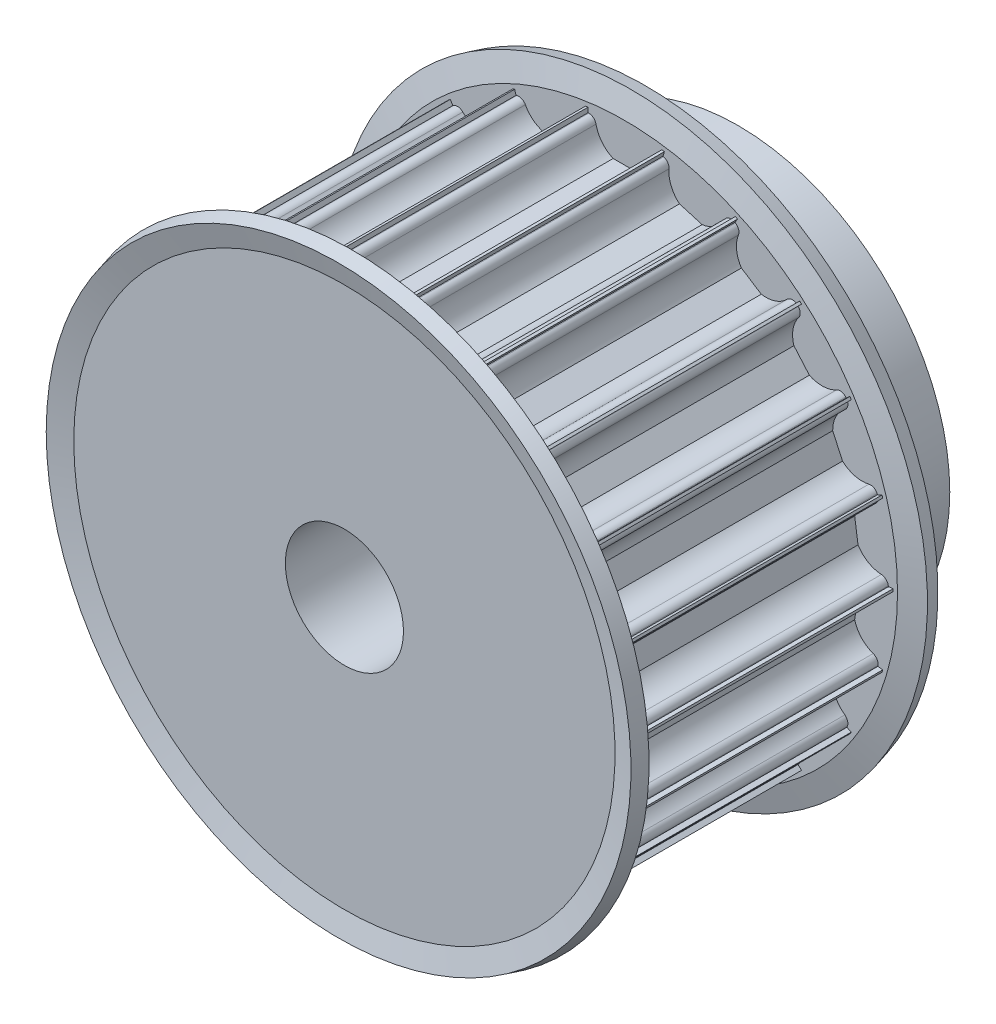
SolidWorks part; units mm, degrees
ref_plane "Front Plane" through (0, 0, 0) normal (0, 0, 1) x (1, 0, 0)
ref_plane "Top Plane" through (0, 0, 0) normal (0, 1, 0) x (1, 0, 0)
ref_plane "Right Plane" through (0, 0, 0) normal (1, 0, 0) x (0, 0, -1)
sketch "Sketch1" plane through (0, 0, 0) normal (1, 0, 0) x (0, 0, -1)
  line L0 (0, 0) -> (61.9374, 0) construction
  line L1 (0, 6) -> (0, 27.25)
  line L2 (0, 27.25) -> (30, 27.25)
  line L3 (30, 27.25) -> (30, 21.5)
  line L4 (30, 21.5) -> (40, 21.5)
  line L5 (40, 21.5) -> (40, 6)
  line L6 (40, 6) -> (0, 6)
  dimension "D1" = 27.25
  dimension "D2" = 30
  dimension "D3" = 10
  dimension "D4" = 6
  dimension "D5" = 15.5
revolve "Revolve1" add sketch "Sketch1" angle 360 about L0
sketch "Sketch2" plane through (0, 0, 0) normal (0, 0, 1) x (1, 0, 0)
  line L0 (-3.6742, 26.5) -> (-3.75, 26.5)
  line L1 (-3.75, 26.5) -> (-3.75, 28.5)
  line L2 (-3.75, 28.5) -> (3.75, 28.5)
  line L3 (3.75, 28.5) -> (3.75, 26.5)
  line L4 (3.75, 26.5) -> (3.6742, 26.5)
  line L5 (1.199, 23.75) -> (-1.199, 23.75)
  arc A0 (2.9394, 25.9) -> (1.199, 23.75) centre (0, 26.5) cw
  arc A1 (2.9394, 25.9) -> (3.6742, 26.5) centre (3.6742, 25.75) cw
  arc A2 (-2.9394, 25.9) -> (-3.6742, 26.5) centre (-3.6742, 25.75) ccw
  arc A3 (-1.199, 23.75) -> (-2.9394, 25.9) centre (0, 26.5) cw
  point P10 (3, 26.5)
  point P13 (-3, 26.5)
  dimension "D1" = 3
  dimension "D6" = 0.75
  dimension "D2" = 26.5
  dimension "D3" = 7.5
  dimension "D4" = 2
  dimension "D5" = 3.75
  dimension "D7" = 2.75
extrude "Cut-Extrude1" cut sketch "Sketch2" against normal up to next
pattern_circular "CirPattern1" count 22 over 360 about axis through (0, 0, 0) along (0, 0, 1) of "Cut-Extrude1"
sketch "Sketch3" plane through (0, 0, 0) normal (1, 0, 0) x (0, 0, -1)
  line L0 (15, -0.1345) -> (15, 26.9539) construction
  line L1 (30, -0.1345) -> (0, -0.1345) construction
  line L2 (30, 26.9539) -> (0, 26.9539) construction
  line L3 (30, 21.5) -> (30, 27.4925)
  line L4 (30, 27.4925) -> (30.592, 29.7018)
  line L5 (30.592, 29.7018) -> (29.1431, 30.09)
  line L6 (29.1431, 30.09) -> (28.5, 27.69)
  line L7 (28.5, 27.69) -> (28.5, 21.5)
  line L8 (28.5, 21.5) -> (30, 21.5)
  line L9 (40, 21.5) -> (30, 21.5) construction
  line L10 (1.5, 27.69) -> (1.5, 21.5)
  line L11 (0.8569, 30.09) -> (1.5, 27.69)
  line L12 (-0.592, 29.7018) -> (0.8569, 30.09)
  line L13 (0, 27.4925) -> (-0.592, 29.7018)
  line L14 (0, 21.5) -> (0, 27.4925)
  line L15 (1.5, 21.5) -> (0, 21.5)
  line L16 (0, 0) -> (-13.4738, 0) construction
  dimension "D1" = 15
  dimension "D2" = 1.5
  dimension "D3" = 6.19
  dimension "D4" = 2.4
  dimension "D5" = 1.5
revolve "Revolve2" add sketch "Sketch3" angle 360 about L16
